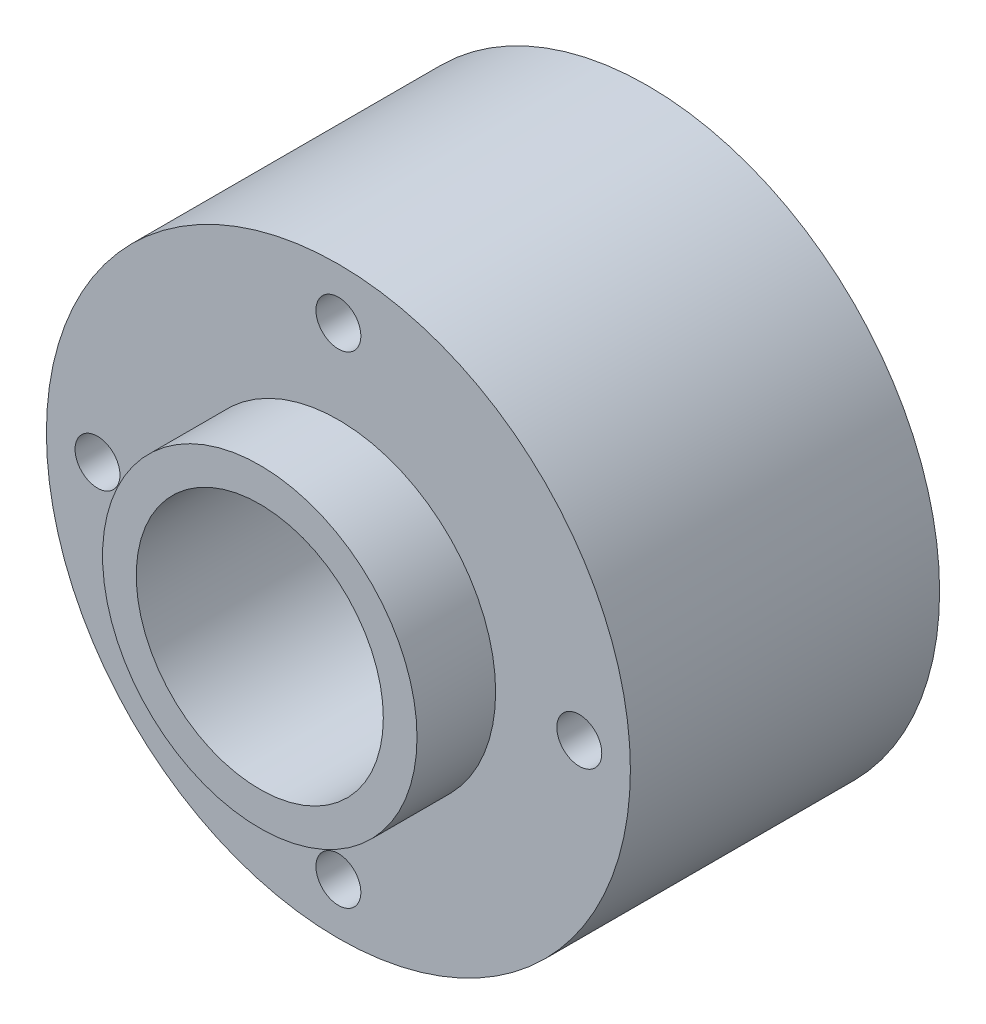
SolidWorks part; units mm, degrees
ref_plane "Front Plane" through (0, 0, 0) normal (0, 0, 1) x (1, 0, 0)
ref_plane "Top Plane" through (0, 0, 0) normal (0, 1, 0) x (1, 0, 0)
ref_plane "Right Plane" through (0, 0, 0) normal (1, 0, 0) x (0, 0, -1)
sketch "Sketch1" plane through (0, 0, 0) normal (0, 0, 1) x (1, 0, 0)
  circle A0 centre (0, 0) radius 26
  circle A1 centre (21.45, 0) radius 2 construction
  circle A2 centre (0, -21.45) radius 2 construction
  circle A3 centre (0, 0) radius 14 construction
  circle A4 centre (-21.45, 0) radius 2 construction
  circle A5 centre (0, 21.45) radius 2 construction
  circle A6 centre (21.45, 0) radius 2
  circle A7 centre (0, -21.45) radius 2
  circle A8 centre (0, 0) radius 14
  circle A9 centre (-21.45, 0) radius 2
  circle A10 centre (0, 21.45) radius 2
  dimension "D1" = 52
extrude "Boss-Extrude1" add sketch "Sketch1" against normal up to surface (27.5315 mm away) from offset 4.5 offset against normal yes
sketch "Sketch3" plane through (0, 0, -4.5) normal (0, 0, 1) x (1, 0, 0)
  circle A0 centre (0, 0) radius 11
  circle A1 centre (0, 0) radius 14 construction
  circle A2 centre (0, 0) radius 14
  dimension "D1" = 22
extrude "Boss-Extrude2" add sketch "Sketch3" against normal blind 34 and the other way blind 7
